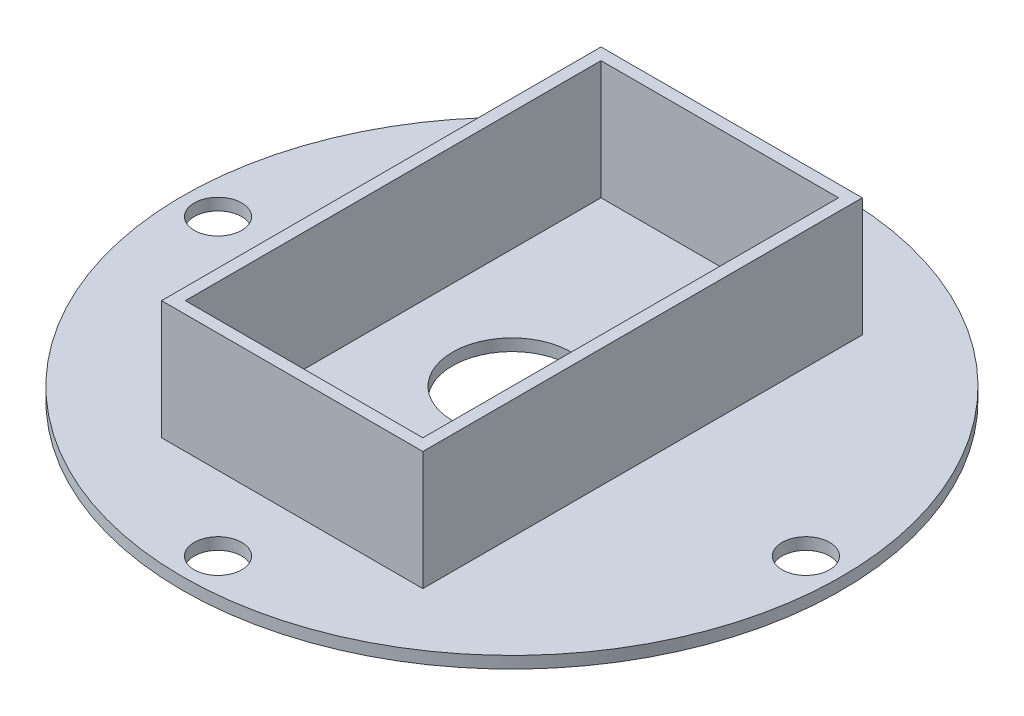
SolidWorks part; units mm, degrees
ref_plane "Front Plane" through (0, 0, 0) normal (0, 0, 1) x (1, 0, 0)
ref_plane "Top Plane" through (0, 0, 0) normal (0, 1, 0) x (1, 0, 0)
ref_plane "Right Plane" through (0, 0, 0) normal (1, 0, 0) x (0, 0, -1)
sketch "Sketch1" plane through (0, 0, 0) normal (0, 1, 0) x (1, 0, 0)
  circle A0 centre (0, 0) radius 55.5
  circle A5 centre (0, 49.5) radius 4
  circle A6 centre (49.5, 0) radius 4
  circle A7 centre (-49.5, 0) radius 4
  circle A8 centre (0, -49.5) radius 4
  dimension "D1" = 111
  dimension "D3" = 8
  dimension "D4" = 8
  dimension "D5" = 8
  dimension "D6" = 8
extrude "Boss-Extrude4" add sketch "Sketch1" along normal blind 2
sketch "Sketch6" plane through (0, 2, 0) normal (0, 1, 0) x (1, 0, 0)
  line L1 (-20, 35) -> (20, 35)
  line L2 (-20, 35) -> (-20, -35)
  line L3 (-20, -35) -> (20, -35)
  line L4 (20, 35) -> (20, -35)
  line L5 (-20, 35) -> (20, -35) construction
  line L6 (-20, -35) -> (20, 35) construction
  line L7 (-22, 37) -> (22, 37)
  line L8 (-22, 37) -> (-22, -37)
  line L9 (-22, -37) -> (22, -37)
  line L10 (22, 37) -> (22, -37)
  line L11 (-22, 37) -> (22, -37) construction
  line L12 (-22, -37) -> (22, 37) construction
  point P0 (0, 0)
  point P6 (0, 0)
  dimension "D1" = 70
  dimension "D2" = 40
  dimension "D3" = 74
  dimension "D4" = 44
extrude "Boss-Extrude5" add sketch "Sketch6" along normal blind 20
sketch "Sketch7" plane through (0, 2, 0) normal (0, 1, 0) x (1, 0, 0)
  circle A0 centre (0, 0) radius 10
  dimension "D1" = 20
extrude "Cut-Extrude2" cut sketch "Sketch7" against normal blind 30
